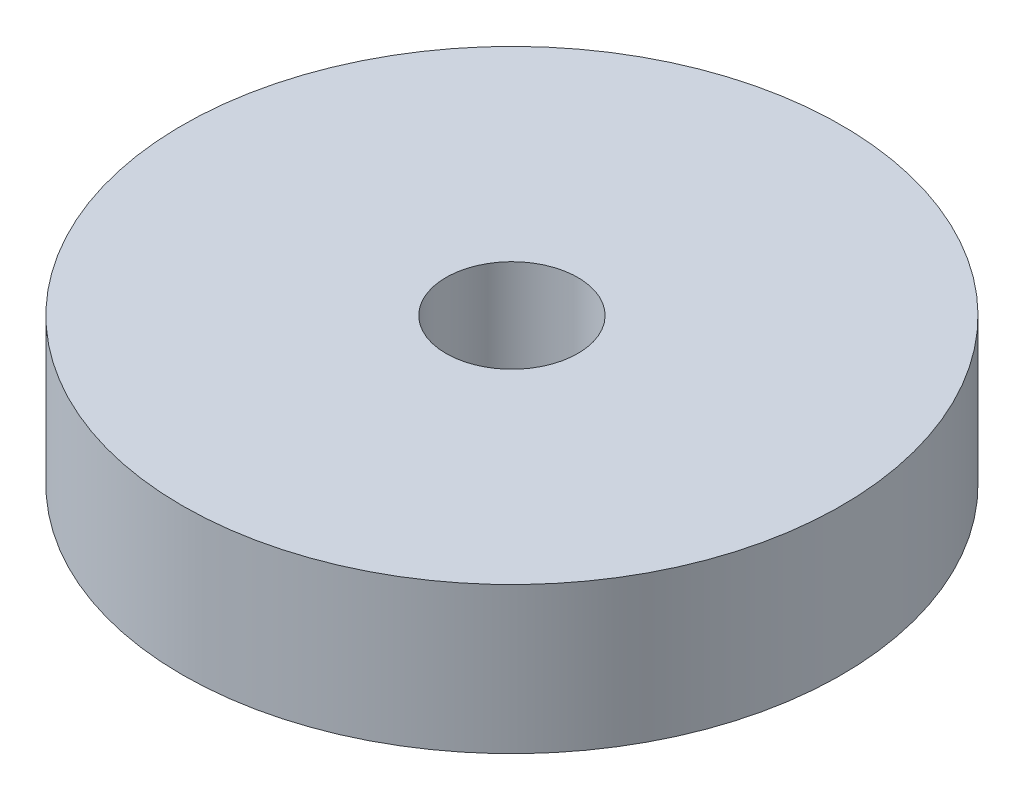
SolidWorks part; units mm, degrees
ref_plane "Front Plane" through (0, 0, 0) normal (0, 0, 1) x (1, 0, 0)
ref_plane "Top Plane" through (0, 0, 0) normal (0, 1, 0) x (1, 0, 0)
ref_plane "Right Plane" through (0, 0, 0) normal (1, 0, 0) x (0, 0, -1)
sketch "Sketch1" plane through (0, 0, 0) normal (0, 1, 0) x (1, 0, 0)
  circle A0 centre (78.0519, -71.4527) radius 4.5
  dimension "D1" = 9
extrude "Boss-Extrude1" add sketch "Sketch1" along normal blind 2 contours A0
sketch "Sketch2" plane through (0, 2, 0) normal (0, 1, 0) x (1, 0, 0)
  circle A0 centre (78.0519, -71.4527) radius 0.9
  dimension "D1" = 1.8
extrude "Cut-Extrude1" cut sketch "Sketch2" against normal blind 2
